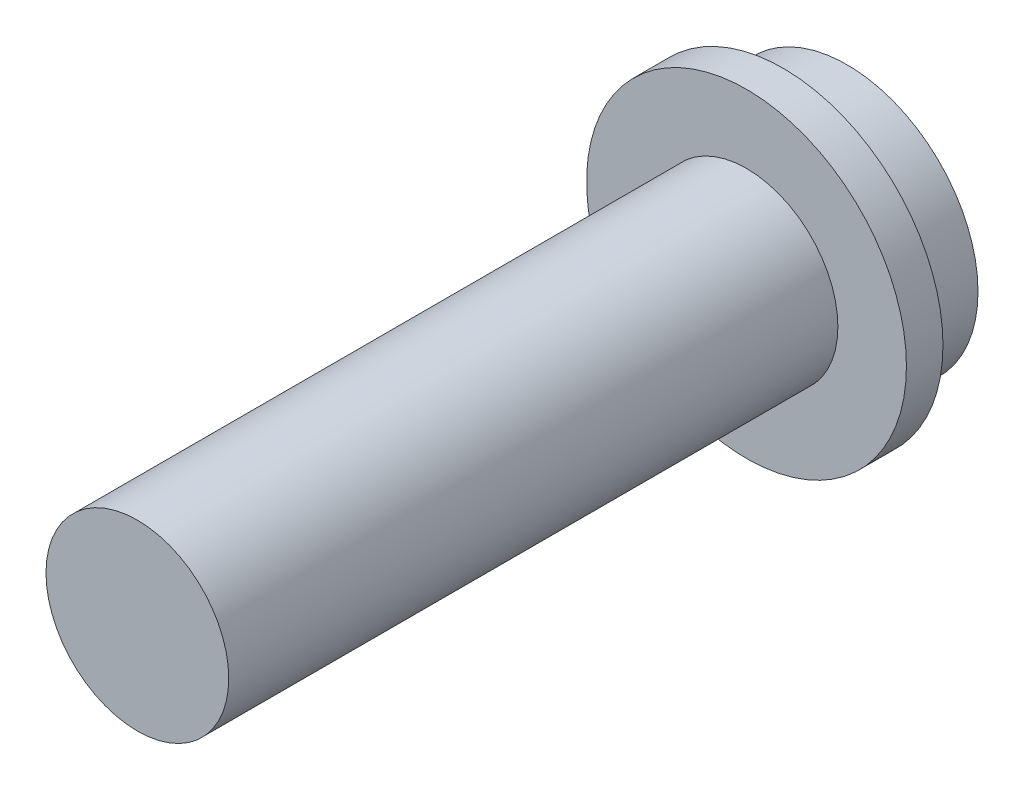
SolidWorks part; units mm, degrees
ref_plane "Front Plane" through (0, 0, 0) normal (0, 0, 1) x (1, 0, 0)
ref_plane "Top Plane" through (0, 0, 0) normal (0, 1, 0) x (1, 0, 0)
ref_plane "Right Plane" through (0, 0, 0) normal (1, 0, 0) x (0, 0, -1)
sketch "S01 - M6 shank" plane through (0, 0, 0) normal (0, 0, 1) x (1, 0, 0)
  circle A0 centre (0, 0) radius 3
extrude "01 - M6 shank" add sketch "S01 - M6 shank" along normal blind 20
sketch "S02 - Head seating diameter" plane through (0, 0, 0) normal (0, 0, 1) x (1, 0, 0)
  circle A0 centre (0, 0) radius 5.25
extrude "02 - Head seating diameter" add sketch "S02 - Head seating diameter" along normal blind 1.2 from offset 1.2
sketch "S03 - Button crown" plane through (0, 0, 0) normal (0, 0, 1) x (1, 0, 0)
  circle A0 centre (0, 0) radius 4.3
extrude "03 - Button crown" add sketch "S03 - Button crown" along normal blind 2.1 from offset 3.3
sketch "S04 - 4 mm hex key" plane through (0, 0, 0) normal (0, 0, 1) x (1, 0, 0)
  line L0 (2.3094, 0) -> (1.1547, 2)
  line L1 (1.1547, 2) -> (-1.1547, 2)
  line L2 (-1.1547, 2) -> (-2.3094, 0)
  line L3 (-2.3094, 0) -> (-1.1547, -2)
  line L4 (-1.1547, -2) -> (1.1547, -2)
  line L5 (1.1547, -2) -> (2.3094, 0)
extrude "04 - 4 mm hex key" cut sketch "S04 - 4 mm hex key" along normal blind 2.2 from offset 3.4
